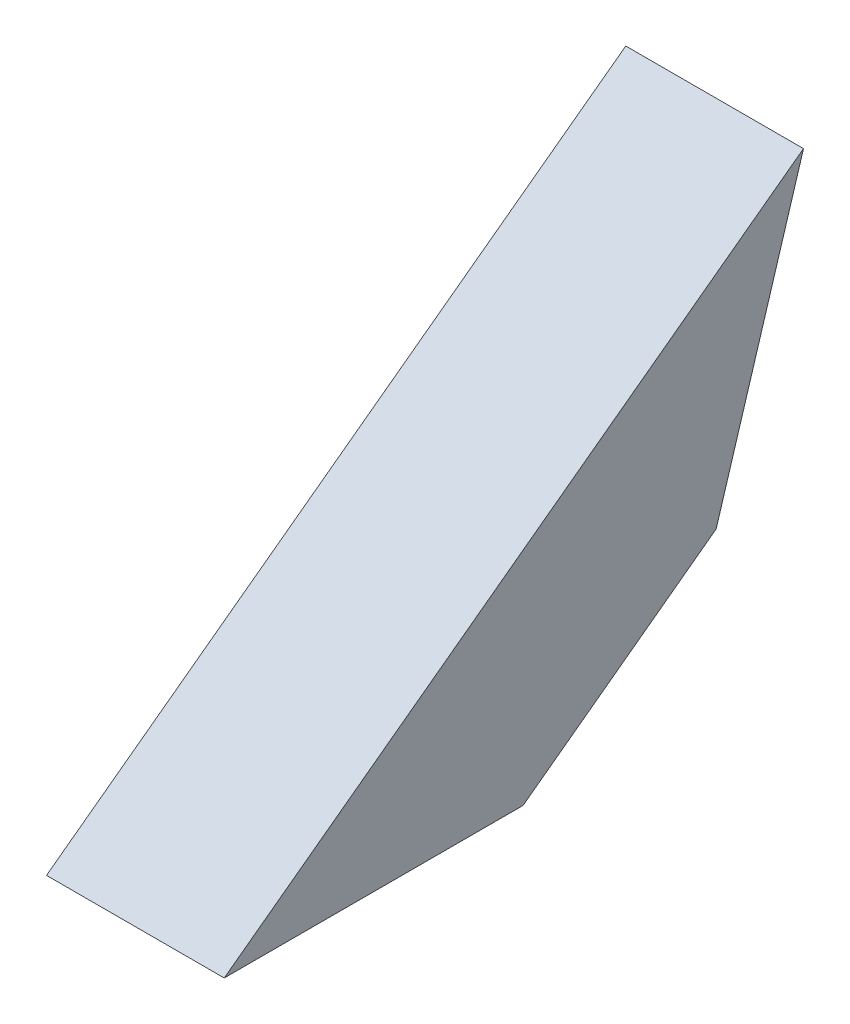
SolidWorks part; units mm, degrees
ref_plane "Front Plane" through (0, 0, 0) normal (0, 0, 1) x (1, 0, 0)
ref_plane "Top Plane" through (0, 0, 0) normal (0, 1, 0) x (1, 0, 0)
ref_plane "Right Plane" through (0, 0, 0) normal (1, 0, 0) x (0, 0, -1)
sketch "Sketch1" plane through (0, 0, 0) normal (1, 0, 0) x (0, 0, -1)
  line L2 (-16.8117, 0) -> (0, 0)
  line L3 (0, 0) -> (10.8635, 8.0386)
  line L4 (10.8635, 8.0386) -> (15.7788, 24.1157)
  line L5 (15.7788, 24.1157) -> (-16.8117, 0)
  line L6 (10.8635, 8.0386) -> (8.4059, 0) construction
  line L7 (8.4059, 0) -> (0, 0) construction
  dimension "D1" = 107
  dimension "D2" = 107
  dimension "D3" = 5
  dimension "D4" = 10
extrude "Boss-Extrude1" add sketch "Sketch1" along normal blind 10
equation "\"D2@Sketch1\"=\"D1@Sketch1\""
